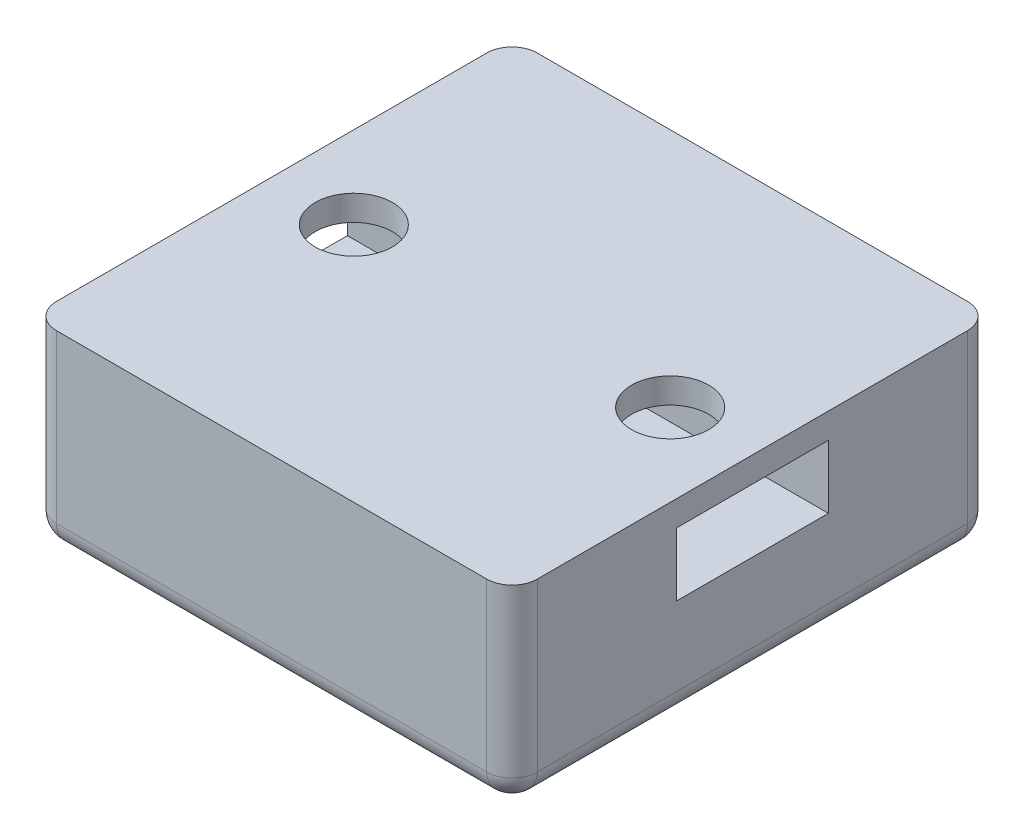
SolidWorks part; units mm, degrees
ref_plane "Front Plane" through (0, 0, 0) normal (0, 0, 1) x (1, 0, 0)
ref_plane "Top Plane" through (0, 0, 0) normal (0, 1, 0) x (1, 0, 0)
ref_plane "Right Plane" through (0, 0, 0) normal (1, 0, 0) x (0, 0, -1)
sketch "Sketch1" plane through (0, 0, 0) normal (0, 1, 0) x (1, 0, 0)
  line L0 (0, 0) -> (19, 0)
  line L1 (0, 0) -> (0, 19)
  line L2 (19, 0) -> (19, 19)
  line L3 (0, 19) -> (19, 19)
  dimension "D1" = 19
extrude "Boss-Extrude1" add sketch "Sketch1" along normal blind 7.6
sketch "Sketch2" plane through (19, 0, 0) normal (1, 0, 0) x (0, 0, -1)
  line L0 (0, 7.6) -> (19, 7.6) construction
  line L15 (6.5, 6.6) -> (12.5, 6.6)
  line L16 (6.5, 6.6) -> (6.5, 4.1)
  line L17 (6.5, 4.1) -> (12.5, 4.1)
  line L18 (12.5, 6.6) -> (12.5, 4.1)
  line L21 (6.5, 6.6) -> (12.5, 4.1) construction
  line L22 (12.5, 6.6) -> (6.5, 4.1) construction
  line L23 (0, 5.35) -> (19, 5.35) construction
  line L24 (19, 7.6) -> (19, 0) construction
  line L25 (0, 7.6) -> (0, 0) construction
  point P6 (0, 6.75)
  point P10 (9.5, 5.35)
  point P13 (9.5, 5.35)
  dimension "D1" = 6
  dimension "D2" = 2.5
  dimension "D3" = 1
extrude "Cut-Extrude1" cut sketch "Sketch2" against normal up to next
sketch "Sketch3" plane through (0, 7.6, 0) normal (0, 1, 0) x (1, 0, 0)
  line L0 (9.5, 19) -> (9.5, 0) construction
  line L1 (19, 19) -> (0, 19) construction
  line L2 (0, 0) -> (19, 0) construction
  line L3 (3.25, 0) -> (3.25, 19) construction
  line L5 (0, 19) -> (0, 0) construction
  circle A0 centre (3.25, 9.5) radius 1.525
  circle A1 centre (15.75, 9.5) radius 1.525
  point P8 (0, 0)
  point P19 (3.25, 9.5)
  dimension "D2" = 3.05
  dimension "D1" = 3.25
extrude "Cut-Extrude2" cut sketch "Sketch3" against normal up to next
sketch "Sketch4" plane through (0, 0, 0) normal (0, -1, 0) x (1, 0, 0)
  line L0 (19, -19) -> (0, 0) construction
  line L1 (19, 0) -> (19, -19) construction
  line L2 (19, -19) -> (0, -19) construction
  line L3 (0, -19) -> (19, 0) construction
  circle A1 centre (9.5, -9.5) radius 5.05
  dimension "D1" = 10.1
extrude "Cut-Extrude3" cut sketch "Sketch4" against normal blind 3.1
fillet "Fillet1" radius 1 4 edges at (0, 3.8, -19) (19, 3.8, -19) (0, 3.8, 0) (19, 3.8, 0)
fillet "Fillet2" radius 1 9 edges at (0.2929, 0, -0.2929) (9.5, 0, 0) (18.7071, 0, -0.2929) (19, 0, -9.5) (18.7071, 0, -18.7071) (9.5, 0, -19) (0.2929, 0, -18.7071) (0, 0, -9.5) (9.5, 0, -14.55)
sketch "Sketch5" plane through (0, 3.1, 0) normal (0, -1, 0) x (1, 0, 0)
  circle A0 centre (9.5, -9.5) radius 1.55
  dimension "D1" = 3.1
extrude "Cut-Extrude4" cut sketch "Sketch5" against normal up to next
